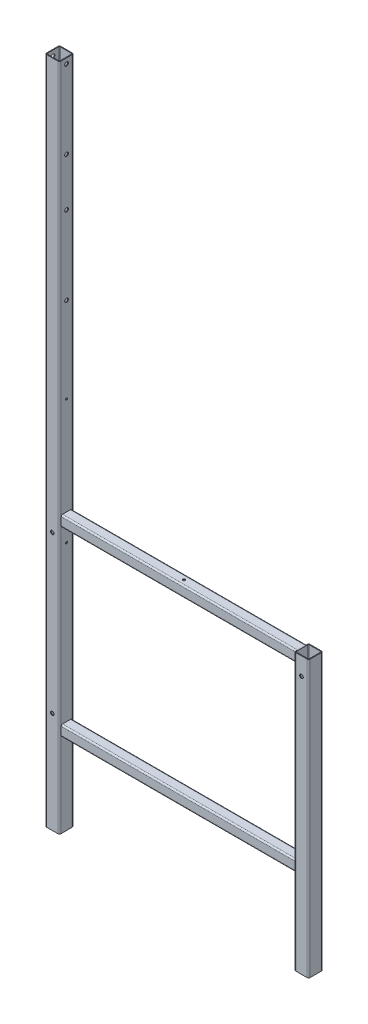
SolidWorks part; units mm, degrees
other "DetailItem1"
other "DetailItem2"
other "DetailItem3"
other "DetailItem4"
other "Weld Folder"
other "Weld Bead1"
other "Weld Bead2"
other "Weld Bead3"
other "Weld Bead4"
material "AISI 304"
ref_plane "Front Plane" through (0, 0, 0) normal (0, 0, 1) x (1, 0, 0)
ref_plane "Top Plane" through (0, 0, 0) normal (0, 1, 0) x (1, 0, 0)
ref_plane "Right Plane" through (0, 0, 0) normal (1, 0, 0) x (0, 0, -1)
sketch3d "3DStructure"
  line L0 (0, 0, 0) -> (0, 1880, 0)
  line L1 (700, 760, 0) -> (0, 760, 0)
  line L2 (700, 760, 0) -> (700, 0, 0)
  line L5 (0, 250, 0) -> (700, 250, 0)
  dimension "LegHeight" = 760
  dimension "D3" = 250
  dimension "D1" = 700
  dimension "D4" = 1880
other "Square tube - configured 40 X 40 X 2(1)"
ref_plane "Plane1" through (0, 0, 0) normal (0, 1, 0) x (1, 0, 0)
sketch "Sketch1" plane through (0, 0, 0) normal (0, 1, 0) x (1, 0, 0)
  line L0 (-16, -18) -> (16, -18)
  line L1 (-18, -16) -> (-18, 16)
  line L2 (16, 18) -> (-16, 18)
  line L3 (18, 16) -> (18, -16)
  line L4 (-16, -20) -> (16, -20)
  line L5 (-20, -16) -> (-20, 16)
  line L6 (16, 20) -> (-16, 20)
  line L7 (20, 16) -> (20, -16)
  arc A0 (20, 16) -> (16, 20) centre (16, 16) ccw
  arc A1 (16, -20) -> (20, -16) centre (16, -16) ccw
  arc A2 (-20, -16) -> (-16, -20) centre (-16, -16) ccw
  arc A3 (-16, 20) -> (-20, 16) centre (-16, 16) ccw
  arc A4 (-16, 18) -> (-18, 16) centre (-16, 16) ccw
  arc A5 (18, 16) -> (16, 18) centre (16, 16) ccw
  arc A6 (16, -18) -> (18, -16) centre (16, -16) ccw
  arc A7 (-18, -16) -> (-16, -18) centre (-16, -16) ccw
  point P0 (-20, 0)
  point P1 (20, 0)
  point P2 (0, 20)
  point P3 (0, -20)
  point P4 (0, 0)
  point P5 (-20, -20)
  point P6 (20, -20)
  point P7 (20, 20)
  point P8 (-20, 20)
  point P33 (0, 0)
  dimension "D1" = 4
  dimension "Thickness" = 2
  dimension "V_leg" = 40
other "Square tube - configured 20 X 20 X 2(1)"
ref_plane "Plane2" through (700, 760, 0) normal (-1, 0, 0) x (0, 0, 1)
sketch "Sketch11" plane through (700, 760, 0) normal (-1, 0, 0) x (0, 0, 1)
  line L0 (-11, -13) -> (11, -13)
  line L1 (-13, -11) -> (-13, 11)
  line L2 (11, 13) -> (-11, 13)
  line L3 (13, 11) -> (13, -11)
  line L4 (-11, -15) -> (11, -15)
  line L5 (-15, -11) -> (-15, 11)
  line L6 (11, 15) -> (-11, 15)
  line L7 (15, 11) -> (15, -11)
  arc A0 (15, 11) -> (11, 15) centre (11, 11) ccw
  arc A1 (11, -15) -> (15, -11) centre (11, -11) ccw
  arc A2 (-15, -11) -> (-11, -15) centre (-11, -11) ccw
  arc A3 (-11, 15) -> (-15, 11) centre (-11, 11) ccw
  arc A4 (-11, 13) -> (-13, 11) centre (-11, 11) ccw
  arc A5 (13, 11) -> (11, 13) centre (11, 11) ccw
  arc A6 (11, -13) -> (13, -11) centre (11, -11) ccw
  arc A7 (-13, -11) -> (-11, -13) centre (-11, -11) ccw
  point P0 (-15, 0)
  point P1 (15, 0)
  point P2 (0, 15)
  point P3 (0, -15)
  point P4 (0, 0)
  point P5 (-15, -15)
  point P6 (15, -15)
  point P7 (15, 15)
  point P8 (-15, 15)
  point P33 (0, 0)
  dimension "D1" = 4
  dimension "Thickness" = 2
  dimension "V_leg" = 30
other "Trim/Extend1"
other "Trim/Extend2"
other "Trim/Extend3"
hole_wizard "Ø10.2 (10.2) Frame Together" positions "Sketch2" profile "Sketch3" hole size "Ø10.2" standard "ANSI Metric" end condition through all
sketch "Sketch2" plane through (0, 0, 20) normal (0, 0, 1) x (1, 0, 0)
  line L0 (700, 800) -> (700, 778.1162) construction
  line L6 (0, 1880) -> (0, 770.345) construction
  line L7 (-16, 1880) -> (16, 1880) construction
  line L8 (-16, 0) -> (16, 0) construction
  line L10 (684, 775) -> (716, 775) construction
  point P0 (700, 725)
  point P25 (0, 725)
  point P33 (0, 285)
  point P47 (700, 775)
  dimension "D1" = 50
  dimension "D2" = 285
sketch "Sketch3" plane through (700, 725, 20) normal (1, 0, 0) x (0, -1, 0)
  line L0 (0, 0) -> (0, 40)
  line L1 (0, 40) -> (5.1, 40)
  line L2 (5.1, 40) -> (5.1, 0)
  line L5 (5.1, 0) -> (0, 0)
  line L11 (0, -6.35) -> (0, 107.95) construction
  dimension "Thru Hole Dia." = 10.2
  dimension "Thru Hole Depth" = 40
hole_wizard "Ø10.5 (10.5) Shelf Holes" positions "Sketch4" profile "Sketch5" hole size "Ø10.5" standard "ANSI Metric" end condition through all
sketch "Sketch4" plane through (-20, 0, 0) normal (-1, 0, 0) x (0, 0, 1)
  line L0 (-16, 0) -> (16, 0) construction
  point P0 (0, 1290)
  point P7 (0, 1510)
  point P11 (0, 1645)
  point P13 (0, 1865)
  dimension "D1" = 1290
  dimension "D2" = 220
  dimension "D4" = 220
  dimension "D3" = 355
sketch "Sketch5" plane through (-20, 1290, 0) normal (0, 1, 0) x (0, 0, 1)
  line L0 (0, 0) -> (0, 740)
  line L1 (0, 740) -> (5.25, 740)
  line L2 (5.25, 740) -> (5.25, 0)
  line L5 (5.25, 0) -> (0, 0)
  line L11 (0, -6.35) -> (0, 107.95) construction
  dimension "Thru Hole Dia." = 10.5
  dimension "Thru Hole Depth" = 740
hole_wizard "Ø10.5 (10.5) PC Shelf Hole" [suppressed] positions "Sketch6" profile "Sketch7" hole size "Ø10.5" standard "ANSI Metric"
sketch "Sketch6" plane through (0, 0, 15) normal (0, 0, 1) x (1, 0, 0)
  line L1 (680, 725) -> (680, 0) construction
  line L2 (680, 239) -> (680, 261) construction
  point P0 (580, 250)
  point P13 (680, 250)
  dimension "D1" = 100
sketch "Sketch7" plane through (580, 250, 15) normal (1, 0, 0) x (0, -1, 0)
  line L0 (0, 0) -> (0, 35)
  line L1 (0, 35) -> (5.25, 35)
  line L2 (5.25, 35) -> (5.25, 0)
  line L5 (5.25, 0) -> (0, 0)
  line L11 (0, -6.35) -> (0, 107.95) construction
  dimension "Thru Hole Dia." = 10.5
  dimension "Thru Hole Depth" = 35
hole_wizard "Ø5.2 (5.2) Vertical Wall Holes" positions "Sketch8" profile "Sketch9" hole size "Ø5.2" standard "ANSI Metric"
sketch "Sketch8" plane through (-20, 0, 0) normal (-1, 0, 0) x (0, 0, 1)
  line L0 (-16, 0) -> (16, 0) construction
  point P0 (0, 700)
  point P2 (0, 1050)
  dimension "D1" = 700
  dimension "D2" = 350
sketch "Sketch9" plane through (-20, 700, 0) normal (0, 1, 0) x (0, 0, 1)
  line L0 (0, 0) -> (0, 51.5622)
  line L1 (0, 51.5622) -> (2.6, 50)
  line L2 (2.6, 50) -> (2.6, 0)
  line L5 (2.6, 0) -> (0, 0)
  line L10 (0, 51.5622) -> (-2.6, 50) construction
  line L11 (0, -6.35) -> (0, 107.95) construction
  dimension "Hole Dia." = 5.2
  dimension "Hole Depth" = 50
  dimension "Drill Angle" = 118
hole_wizard "M6 Clearance Hole for table" positions "Sketch12" profile "Sketch13" hole size "M6" standard "ANSI Metric"
sketch "Sketch12" plane through (0, 775, 0) normal (0, 1, 0) x (1, 0, 0)
  line L0 (720, -16) -> (720, 16) construction
  point P0 (350, 0)
  dimension "D1" = 370
sketch "Sketch13" plane through (350, 775, 0) normal (1, 0, 0) x (0, 0, 1)
  line L0 (0, 0) -> (0, 36.9828)
  line L1 (0, 36.9828) -> (3.3, 35)
  line L2 (3.3, 35) -> (3.3, 0)
  line L5 (3.3, 0) -> (0, 0)
  line L10 (0, 36.9828) -> (-3.3, 35) construction
  line L11 (0, -6.35) -> (0, 107.95) construction
  dimension "Hole Dia." = 6.6
  dimension "Hole Depth" = 35
  dimension "Drill Angle" = 118
equation "\"D4@Sketch4\"=\"D2@Sketch4\""
equation "\"LegHeight\"= \"LegHeight@3DStructure\""
